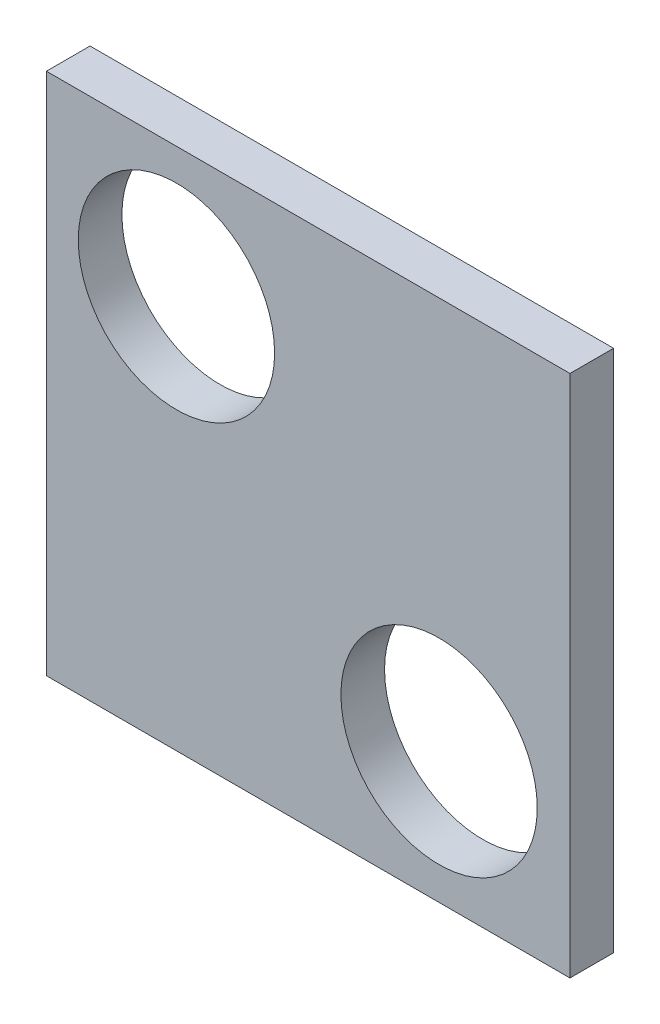
SolidWorks part; units mm, degrees
ref_plane "Front Plane" through (0, 0, 0) normal (0, 0, 1) x (1, 0, 0)
ref_plane "Top Plane" through (0, 0, 0) normal (0, 1, 0) x (1, 0, 0)
ref_plane "Right Plane" through (0, 0, 0) normal (1, 0, 0) x (0, 0, -1)
sketch "Sketch2" plane through (0, 0, 0) normal (0, 0, 1) x (1, 0, 0)
  line L0 (0.7451, 2.2549) -> (0.7451, 3) construction
  line L1 (0, 0) -> (3, 0)
  line L2 (0, 0) -> (0, 3)
  line L3 (0, 3) -> (3, 3)
  line L4 (3, 0) -> (3, 3)
  line L6 (0, 2.2549) -> (0.7451, 2.2549) construction
  circle A0 centre (0.7451, 2.2549) radius 0.5625
  point P9 (1.5, 1.5)
  point P10 (1.5, 1.5)
  point P11 (0, 0)
  point P12 (0.607, 3)
  point P13 (0, 0)
  point P14 (0, 2.1009)
  dimension "D3" = 1.125
  dimension "D1" = 3
  dimension "D2" = 0.7451
extrude "Boss-Extrude1" add sketch "Sketch2" along normal blind 0.25
sketch "Sketch5" plane through (0, 0, 0.25) normal (0, 0, 1) x (1, 0, 0)
  line L0 (2.25, 0.75) -> (3, 0.75) construction
  line L1 (3, 0) -> (3, 3) construction
  line L2 (2.25, 0.75) -> (2.25, 0) construction
  line L3 (0, 0) -> (3, 0) construction
  circle A0 centre (2.25, 0.75) radius 0.5625
  circle A1 centre (0.7451, 2.2549) radius 0.5625 construction
  dimension "D1" = 1.125
  dimension "D2" = 0.75
extrude "Cut-Extrude1" cut sketch "Sketch5" against normal through all
